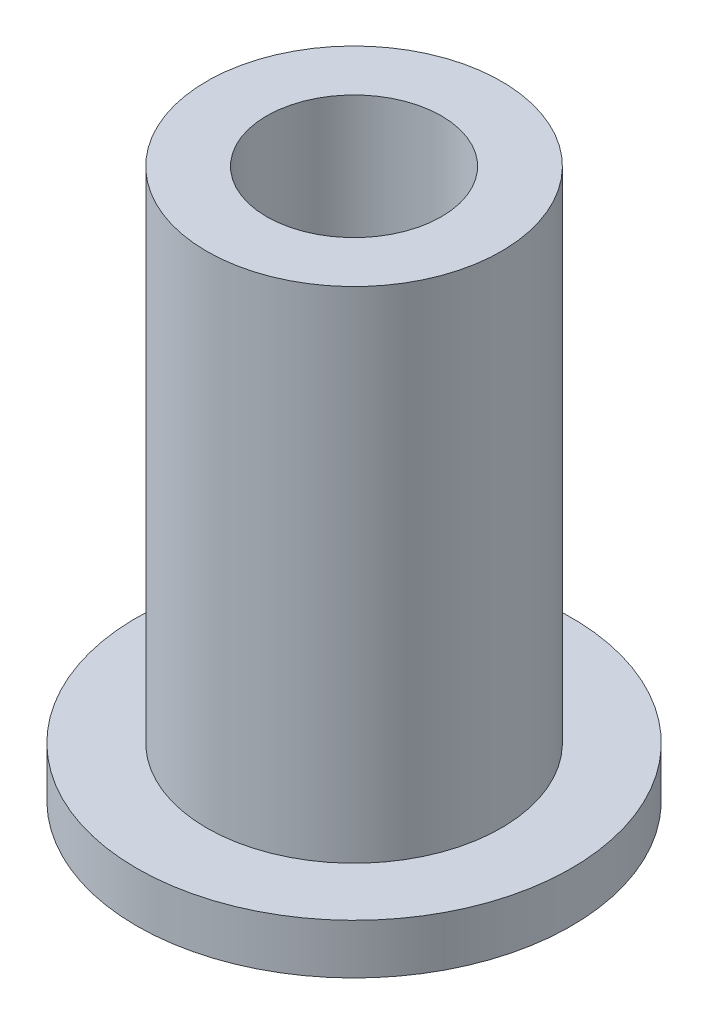
SolidWorks part; units mm, degrees
ref_plane "Front Plane" through (0, 0, 0) normal (0, 0, 1) x (1, 0, 0)
ref_plane "Top Plane" through (0, 0, 0) normal (0, 1, 0) x (1, 0, 0)
ref_plane "Right Plane" through (0, 0, 0) normal (1, 0, 0) x (0, 0, -1)
sketch "Sketch1" plane through (0, 0, 0) normal (0, 1, 0) x (1, 0, 0)
  circle A0 centre (0, 0) radius 4.35
  dimension "D1" = 8.7
extrude "Boss-Extrude1" add sketch "Sketch1" along normal blind 1
sketch "Sketch2" plane through (0, 1, 0) normal (0, 1, 0) x (1, 0, 0)
  circle A0 centre (0, 0) radius 2.95
  dimension "D1" = 5.9
extrude "Boss-Extrude2" add sketch "Sketch2" along normal blind 10
sketch "Sketch3" plane through (0, 11, 0) normal (0, 1, 0) x (1, 0, 0)
  circle A0 centre (0, 0) radius 1.75
  dimension "D1" = 3.5
extrude "Cut-Extrude1" cut sketch "Sketch3" against normal through all
